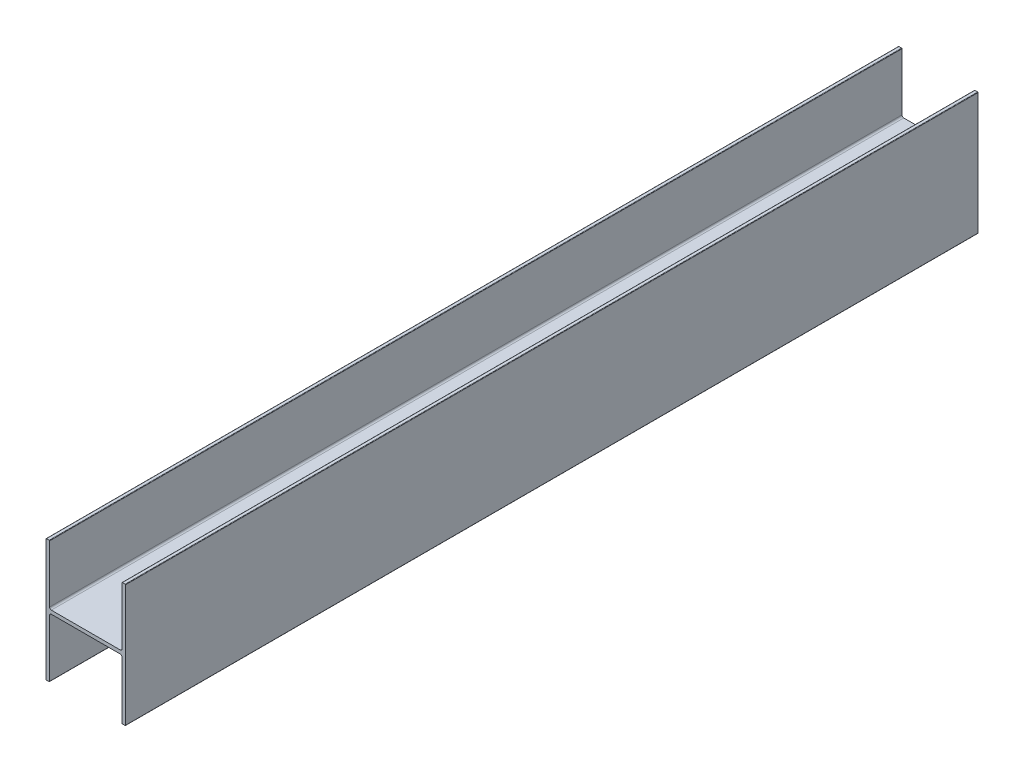
SolidWorks part; units mm, degrees
ref_plane "Front" through (0, 0, 0) normal (0, 0, 1) x (1, 0, 0)
ref_plane "Top" through (0, 0, 0) normal (0, 1, 0) x (1, 0, 0)
ref_plane "Right" through (0, 0, 0) normal (1, 0, 0) x (0, 0, -1)
sketch "Sketch1" plane through (0, 0, 0) normal (0, 0, 1) x (1, 0, 0)
  line L0 (14.224, -21.8948) -> (14.224, 21.8948) construction
  line L1 (-14.224, 21.8948) -> (-14.224, -21.8948) construction
  line L2 (14.224, 0) -> (-14.224, 0) construction
  line L3 (-14.224, -21.8948) -> (-12.954, -21.8948) construction
  line L4 (14.224, -21.8948) -> (12.954, -21.8948) construction
  dimension "Outside Height" = 43.7896
  dimension "Wall Thickness" = 1.27
  dimension "Inside Width" = 25.908
  dimension "Outside Width" = 28.448
sketch "Sketch2" plane through (0, 0, 0) normal (1, 0, 0) x (0, 0, -1)
  line L0 (-152.4, 21.8948) -> (152.4, 21.8948) construction
  point P2 (-108.6104, 21.8948)
  point P4 (108.6104, 21.8948)
  dimension "Length" = 304.8
  dimension "D1" = 43.7896
  dimension "D2" = 43.7896
sketch "Sketch3" plane through (0, 0, 0) normal (0, 0, 1) x (1, 0, 0)
  line L0 (14.224, -21.8948) -> (14.224, 21.8948)
  line L1 (14.224, 21.8948) -> (12.954, 21.8948)
  line L2 (12.954, 21.8948) -> (12.954, 0.635)
  line L3 (12.954, 0.635) -> (-12.954, 0.635)
  line L4 (-12.954, 0.635) -> (-12.954, 21.8948)
  line L5 (-12.954, 21.8948) -> (-14.224, 21.8948)
  line L6 (-14.224, 21.8948) -> (-14.224, -21.8948)
  line L7 (-14.224, -21.8948) -> (-12.954, -21.8948)
  line L8 (-12.954, -21.8948) -> (-12.954, -0.635)
  line L9 (-12.954, -0.635) -> (12.954, -0.635)
  line L10 (12.954, -0.635) -> (12.954, -21.8948)
  line L11 (12.954, -21.8948) -> (14.224, -21.8948)
  line L12 (14.224, -21.8948) -> (14.224, 21.8948) construction
  line L13 (0, 0.635) -> (0, -0.635) construction
extrude "Boss-Extrude1" add sketch "Sketch3" along normal up to vertex (152.4 mm away) and the other way up to vertex (152.4 mm away) up to point (0, 21.8948, 152.4) other way up to point (0, 21.8948, -152.4)
fillet "Fillet1" radius 0.635 4 edges at (-12.954, -0.635, 0) (12.954, -0.635, 0) (12.954, 0.635, 0) (-12.954, 0.635, 0)
fillet "Fillet2" radius 0.1588 8 edges at (14.224, -21.8948, 0) (12.954, -21.8948, 0) (-12.954, -21.8948, 0) (-14.224, -21.8948, 0) (14.224, 21.8948, 0) (12.954, 21.8948, 0) (-12.954, 21.8948, 0) (-14.224, 21.8948, 0)
equation "\"D1@Sketch2\" = \"Outside Height@Sketch1\""
equation "\"D2@Sketch2\" = \"D1@Sketch2\""
equation "\"D1@Fillet1\"=\"Wall Thickness@Sketch1\" / 2"
equation "\"D1@Fillet2\"=\"Wall Thickness@Sketch1\" / 8"
